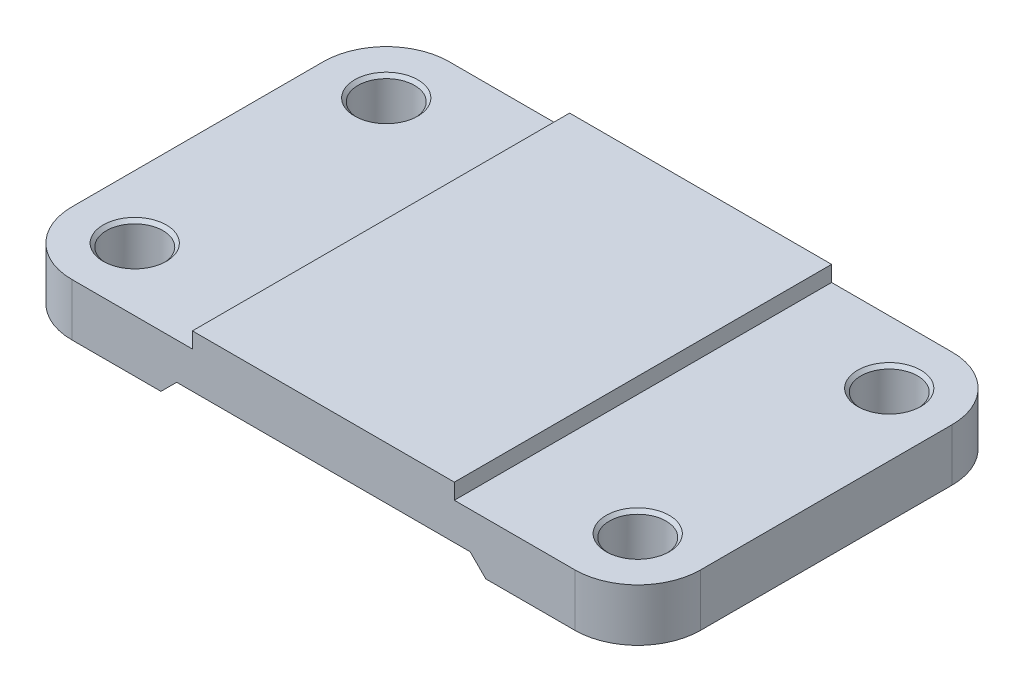
SolidWorks part; units mm, degrees
ref_plane "Front Plane" through (0, 0, 0) normal (0, 0, 1) x (1, 0, 0)
ref_plane "Top Plane" through (0, 0, 0) normal (0, 1, 0) x (1, 0, 0)
ref_plane "Right Plane" through (0, 0, 0) normal (1, 0, 0) x (0, 0, -1)
sketch "Sketch1" plane through (0, 0, 0) normal (0, 0, 1) x (1, 0, 0)
  line L0 (-28, 3) -> (-31, 0)
  line L1 (-31, 0) -> (-60, 0)
  line L2 (-60, 0) -> (-60, 10)
  line L3 (-60, 10) -> (-25, 10)
  line L4 (-25, 10) -> (-25, 13)
  line L5 (0, -55) -> (0, 55) construction
  line L6 (25, 10) -> (25, 13)
  line L7 (60, 10) -> (25, 10)
  line L8 (60, 0) -> (60, 10)
  line L9 (31, 0) -> (60, 0)
  line L10 (28, 3) -> (31, 0)
  line L11 (-25, 13) -> (25, 13)
  line L12 (-28, 3) -> (28, 3)
  dimension "D1" = 62
  dimension "D2" = 135
  dimension "D3" = 50
  dimension "D4" = 3
  dimension "D5" = 3
  dimension "D6" = 10
  dimension "D7" = 120
extrude "Boss-Extrude1" add sketch "Sketch1" along normal mid plane 72
fillet "Fillet1" radius 12 4 edges at (-60, 5, -36) (60, 5, -36) (60, 5, 36) (-60, 5, 36)
hole_wizard "M12x1.25 Tapped Hole1" positions "Sketch2" profile "Sketch3" tap size "M12x1.25" standard "ANSI Metric"
sketch "Sketch2" plane through (0, 10, 0) normal (0, 1, 0) x (1, 0, 0)
  point P0 (-48, 24)
  point P3 (-48, -24)
  point P6 (48, -24)
  point P9 (48, 24)
sketch "Sketch3" plane through (-48, 10, -24) normal (1, 0, 0) x (0, 0, 1)
  line L0 (0, 0) -> (0, 27.75)
  line L1 (0, 27.75) -> (5.4, 24.5054)
  line L2 (5.4, 24.5054) -> (5.4, 0.625)
  line L3 (5.4, 0.625) -> (6.025, 0)
  line L5 (6.025, 0) -> (0, 0)
  line L6 (-5.4, 0.625) -> (-6.025, 0) construction
  line L10 (0, 27.75) -> (-5.4, 24.5054) construction
  line L11 (0, -6.35) -> (0, 107.95) construction
  dimension "Tap Drill Dia." = 10.8
  dimension "Tap Drill Depth" = 27.75
  dimension "Near C'Sink Dia." = 12.05
  dimension "Near C'Sink Angle" = 90
  dimension "Drill Angle" = 118
cosmetic thread "Hole Thread1" parameters "D1"=24, "D2"=12
cosmetic thread "Hole Thread2" parameters "D1"=24, "D2"=12
cosmetic thread "Hole Thread3" parameters "D1"=24, "D2"=12
cosmetic thread "Hole Thread4" parameters "D1"=24, "D2"=12
